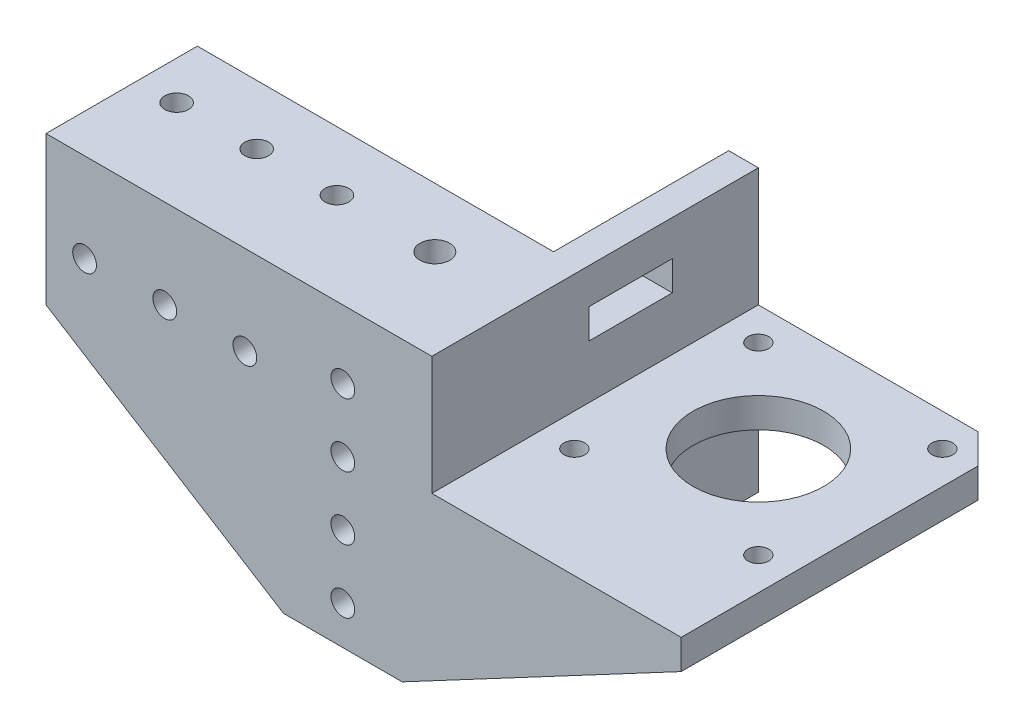
SolidWorks part; units mm, degrees
ref_plane "Front Plane" through (0, 0, 0) normal (0, 0, 1) x (1, 0, 0)
ref_plane "Top Plane" through (0, 0, 0) normal (0, 1, 0) x (1, 0, 0)
ref_plane "Right Plane" through (0, 0, 0) normal (1, 0, 0) x (0, 0, -1)
sketch "Sketch1" plane through (0, 0, 0) normal (0, 0, 1) x (1, 0, 0)
  line L0 (-40, 0) -> (0, -25)
  line L1 (-40, 20) -> (0, 20)
  line L2 (-40, 20) -> (-40, 0)
  line L3 (-40, 0) -> (0, 0)
  line L4 (0, 20) -> (0, 0)
  line L5 (0, 20) -> (20, 20)
  line L6 (0, 20) -> (0, -25)
  line L7 (0, -25) -> (20, -25)
  line L8 (20, 20) -> (20, -25)
  line L9 (20, 20) -> (25, 20)
  line L10 (20, 20) -> (20, 0)
  line L11 (20, 0) -> (25, 0)
  line L12 (25, 20) -> (25, 0)
  line L13 (20, 0) -> (67, 0)
  line L14 (20, 0) -> (20, -5)
  line L15 (20, -5) -> (57.6, -5)
  line L17 (20, -25) -> (67, 0)
  dimension "D1" = 60
  dimension "D2" = 20
  dimension "D3" = 45
  dimension "D4" = 20
  dimension "D5" = 5
  dimension "D6" = 47
  dimension "D7" = 5
  dimension "D8" = 20
extrude "Boss-Extrude1" add sketch "Sketch1" along normal blind 5.5
sketch "Sketch2" plane through (0, 20, 0) normal (0, 1, 0) x (1, 0, 0)
  line L0 (25, -5.5) -> (25, 0) construction
  line L1 (-40, -5.5) -> (25, -5.5)
  line L2 (-40, -5.5) -> (-40, 20)
  line L3 (-40, 20) -> (25, 20)
  line L4 (25, -5.5) -> (25, 20)
  line L5 (-40, 0) -> (25, 0) construction
  dimension "D1" = 20
extrude "Boss-Extrude2" add sketch "Sketch2" along normal blind 5
sketch "Sketch3" plane through (25, 0, 0) normal (1, 0, 0) x (0, 0, -1)
  line L1 (-5.5, 25) -> (49.5, 25)
  line L2 (-5.5, 25) -> (-5.5, 0)
  line L3 (-5.5, 0) -> (49.5, 0)
  line L4 (49.5, 25) -> (49.5, 0)
  line L5 (-5.5, 0) -> (0, 0) construction
  dimension "D1" = 55
extrude "Boss-Extrude3" add sketch "Sketch3" along normal blind 5
sketch "Sketch4" plane through (0, 0, 0) normal (0, 1, 0) x (1, 0, 0)
  line L1 (67, -5.5) -> (25, -5.5)
  line L2 (67, -5.5) -> (67, 49.5)
  line L3 (67, 49.5) -> (25, 49.5)
  line L4 (25, -5.5) -> (25, 49.5)
extrude "Boss-Extrude4" add sketch "Sketch4" along normal blind 5
sketch "Sketch5" plane through (0, 0, 0) normal (0, 0, -1) x (-1, 0, 0)
  line L0 (-20, -25) -> (-20, 20)
  line L7 (-20, -25) -> (0, -25)
  line L8 (0, -25) -> (40, 0)
  line L9 (40, 0) -> (40, 20)
  line L10 (40, 20) -> (-25, 20)
  line L11 (-25, 20) -> (-25, 0)
  line L12 (-25, 0) -> (-67, 0)
  line L13 (-67, 0) -> (-20, -25)
  line L17 (-20, 20) -> (-25, 20)
  line L18 (-25, 20) -> (-25, 0)
  line L19 (-25, 0) -> (-67, 0)
  line L20 (-67, 0) -> (-20, -25)
  dimension "D1" = 0
extrude "Boss-Extrude6" add sketch "Sketch5" along normal blind 7.5
sketch "Sketch6" plane through (0, 0, -7.5) normal (0, 0, -1) x (-1, 0, 0)
  line L0 (-25, 0) -> (-25, -22.3404)
  line L5 (-67, 0) -> (-20, -25)
  line L6 (-20, -25) -> (-20, 20)
  line L7 (-20, 20) -> (-25, 20)
  line L8 (-25, 20) -> (-25, 0)
  line L9 (-25, 0) -> (-67, 0)
  line L10 (-25, -22.3404) -> (-20, -25)
  line L11 (-20, -25) -> (-20, 20)
  line L12 (-20, 20) -> (-25, 20)
  line L13 (-25, 20) -> (-25, 0)
  dimension "D1" = 0
extrude "Boss-Extrude7" add sketch "Sketch6" along normal up to surface (42 mm away) up to face at (40.6667, 10, -49.5)
sketch "Sketch7" plane through (0, 20, 0) normal (0, 1, 0) x (1, 0, 0)
  line L4 (20, 49.5) -> (20, 20)
  line L5 (20, 20) -> (25, 20)
  line L6 (25, 20) -> (25, 49.5)
  line L7 (25, 49.5) -> (20, 49.5)
  line L8 (20, 49.5) -> (20, 20)
  line L9 (20, 20) -> (25, 20)
  line L10 (25, 20) -> (25, 49.5)
  line L11 (25, 49.5) -> (20, 49.5)
  dimension "D1" = 0
extrude "Boss-Extrude8" add sketch "Sketch7" along normal up to surface (5 mm away) up to face at (5, 25, -21.3333)
sketch "Sketch8" plane through (30, 0, 0) normal (1, 0, 0) x (0, 0, -1)
  line L4 (-5.5, 5) -> (49.5, 5)
  line L5 (49.5, 5) -> (49.5, 25)
  line L6 (49.5, 25) -> (-5.5, 25)
  line L7 (-5.5, 25) -> (-5.5, 5)
  line L8 (-5.5, 5) -> (49.5, 5)
  line L9 (49.5, 5) -> (49.5, 25)
  line L10 (49.5, 25) -> (-5.5, 25)
  line L11 (-5.5, 25) -> (-5.5, 5)
  dimension "D1" = 0
extrude "Cut-Extrude1" cut sketch "Sketch8" against normal blind 5
sketch "Sketch9" plane through (0, 25, 0) normal (0, 1, 0) x (1, 0, 0)
  line L0 (0, 0) -> (20, 20) construction
  line L1 (0, 0) -> (20, 0) construction
  line L2 (0, 0) -> (0, 20) construction
  line L3 (0, 20) -> (20, 20) construction
  line L4 (20, 0) -> (20, 20) construction
  line L5 (0, 10) -> (-40, 10) construction
  line L6 (-40, 20) -> (-40, -5.5) construction
  line L7 (-33.5, 10) -> (-40, 20) construction
  line L9 (-6.5, 10) -> (0, 20) construction
  circle A0 centre (10, 10) radius 2.5
  circle A1 centre (-33.5, 10) radius 2
  circle A2 centre (-20, 10) radius 2
  circle A3 centre (-6.5, 10) radius 2
  dimension "D1" = 5
  dimension "D3" = 4
  dimension "D2" = 6.5
extrude "Cut-Extrude2" cut sketch "Sketch9" against normal through all
sketch "Sketch10" plane through (0, 0, 5.5) normal (0, 0, 1) x (1, 0, 0)
  line L0 (20, 20) -> (-40, 20) construction
  line L1 (0, -25) -> (20, -25) construction
  line L2 (0, -25) -> (0, 20) construction
  line L3 (0, 20) -> (20, 20) construction
  line L4 (20, -25) -> (20, 20) construction
  line L5 (10, 20) -> (10, -25) construction
  line L6 (0, 20) -> (-40, 20) construction
  line L7 (0, 20) -> (0, 0) construction
  line L8 (0, 0) -> (-40, 0) construction
  line L9 (-40, 20) -> (-40, 0) construction
  line L10 (10, -25) -> (0, -25) construction
  line L11 (0, -25) -> (10, -18.5) construction
  line L12 (10, 13.5) -> (0, 20) construction
  line L14 (-40, 20) -> (-33.5, 10) construction
  line L15 (-40, 10) -> (0, 10) construction
  line L17 (0, 20) -> (-6.5, 10) construction
  circle A0 centre (-33.5, 10) radius 2
  circle A1 centre (-20, 10) radius 2
  circle A2 centre (-6.5, 10) radius 2
  circle A6 centre (10, -18.5) radius 2
  circle A7 centre (10, -7.8333) radius 2
  circle A8 centre (10, 2.8333) radius 2
  circle A9 centre (10, 13.5) radius 2
  dimension "D2" = 4
  dimension "D4" = 4
  dimension "D1" = 20
  dimension "D3" = 6.5
  dimension "D6" = 6.5
  dimension "D5" = 4
extrude "Cut-Extrude3" cut sketch "Sketch10" against normal through all
sketch "Sketch11" plane through (0, 0, 0) normal (0, -1, 0) x (1, 0, 0)
  line L0 (67, -7.5) -> (67, -49.5) construction
  line L1 (67, -49.5) -> (25, -49.5) construction
  line L2 (25, -7.5) -> (67, -7.5) construction
  line L3 (25, -7.5) -> (25, -49.5) construction
  line L4 (67, -7.5) -> (25, -49.5) construction
  circle A0 centre (61.5, -44) radius 1.75
  circle A1 centre (61.5, -13) radius 1.75
  circle A2 centre (30.5, -13) radius 1.75
  circle A3 centre (30.5, -44) radius 1.75
  circle A4 centre (46, -28.5) radius 11
  dimension "D1" = 5.5
  dimension "D2" = 5.5
  dimension "D3" = 3.5
  dimension "D4" = 5.5
  dimension "D5" = 5.5
  dimension "D6" = 5.5
  dimension "D7" = 5.5
  dimension "D8" = 5.5
  dimension "D9" = 5.5
  dimension "D10" = 22
extrude "Cut-Extrude4" cut sketch "Sketch11" against normal through all both and the other way through all
chamfer "Chamfer1" distance 5 angle 45 1 edges at (67, 2.5, -49.5)
sketch "Sketch12" plane through (25, 0, 0) normal (1, 0, 0) x (0, 0, -1)
  line L0 (49.5, 25) -> (-5.5, 25) construction
  line L1 (21, 19) -> (35, 19)
  line L2 (21, 19) -> (21, 14)
  line L3 (21, 14) -> (35, 14)
  line L4 (35, 19) -> (35, 14)
  line L5 (21, 12) -> (35, 12) construction
  line L6 (21, 12) -> (21, 7) construction
  line L7 (21, 7) -> (35, 7) construction
  line L8 (35, 12) -> (35, 7) construction
  line L9 (49.5, 5) -> (49.5, 25) construction
  dimension "D1" = 5
  dimension "D2" = 5
  dimension "D3" = 6
  dimension "D4" = 2
  dimension "D5" = 14.5
  dimension "D6" = 14
ref_plane "Plane1" through (0, 0, -49.5) normal (0, 0, -1) x (-1, 0, 0)
extrude "Cut-Extrude5" cut sketch "Sketch12" against normal blind 10
